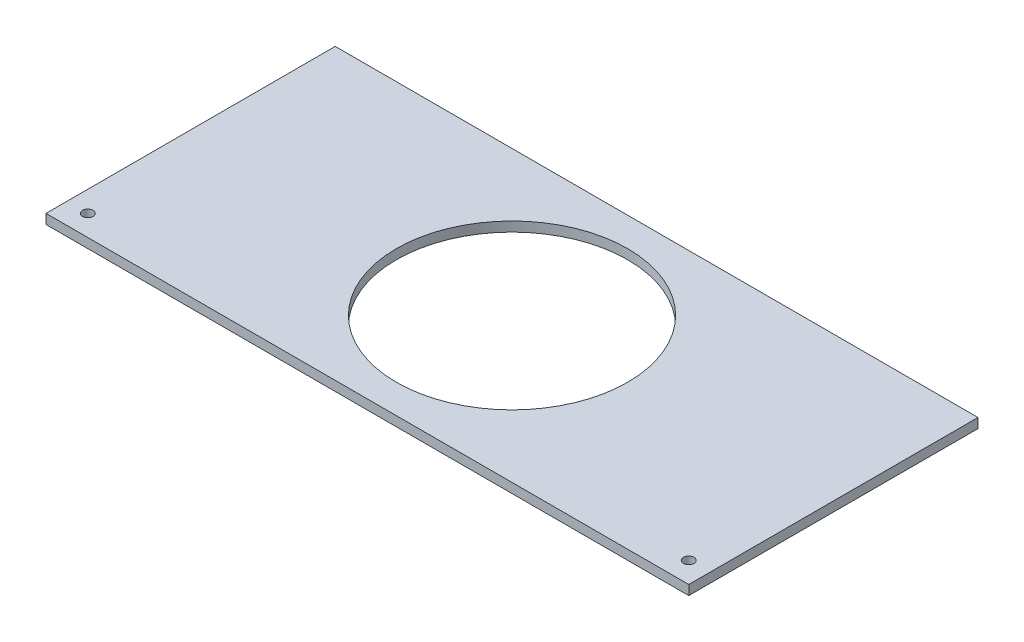
SolidWorks part; units mm, degrees
ref_plane "Front Plane" through (0, 0, 0) normal (0, 0, 1) x (1, 0, 0)
ref_plane "Top Plane" through (0, 0, 0) normal (0, 1, 0) x (1, 0, 0)
ref_plane "Right Plane" through (0, 0, 0) normal (1, 0, 0) x (0, 0, -1)
sketch "Sketch1" plane through (0, 0, 0) normal (0, 1, 0) x (1, 0, 0)
  line L1 (0, 0) -> (200, 0)
  line L2 (0, 0) -> (0, 90)
  line L3 (0, 90) -> (200, 90)
  line L4 (200, 0) -> (200, 90)
  circle A0 centre (100, 45) radius 36
  circle A1 centre (6.5, 6.5) radius 1.65
  circle A2 centre (193.5, 6.5) radius 1.65
extrude "Boss-Extrude1" add sketch "Sketch1" along normal blind 3
